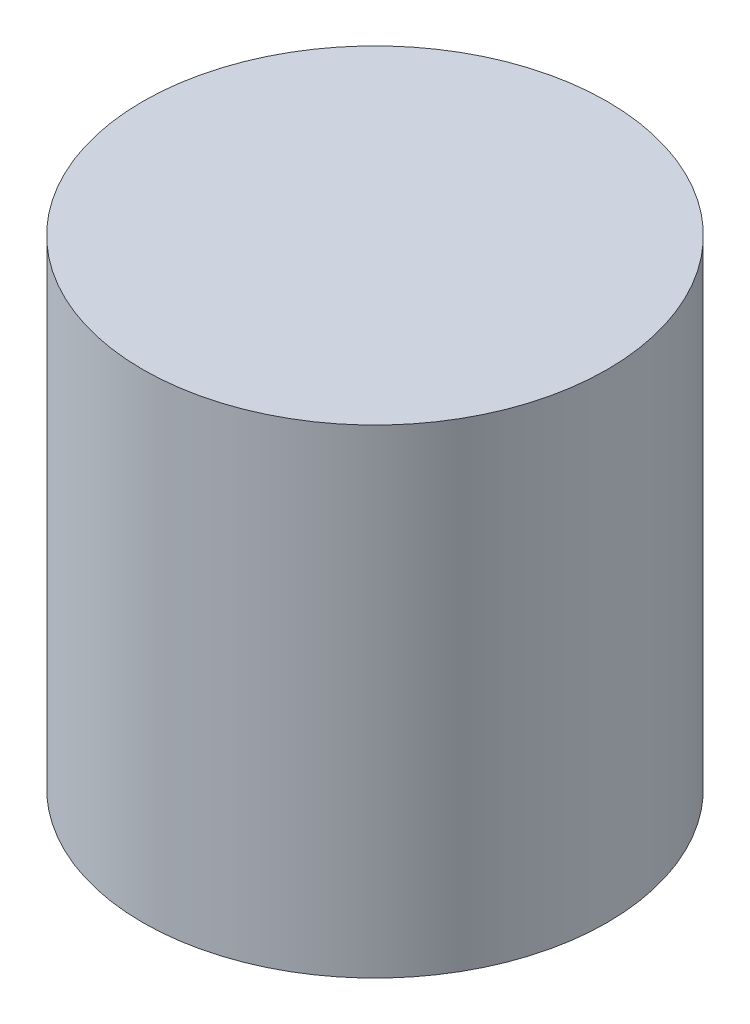
SolidWorks part; units mm, degrees
material "AISI 1035 Steel (SS)"
ref_plane "Front Plane" through (0, 0, 0) normal (0, 0, 1) x (1, 0, 0)
ref_plane "Top Plane" through (0, 0, 0) normal (0, 1, 0) x (1, 0, 0)
ref_plane "Right Plane" through (0, 0, 0) normal (1, 0, 0) x (0, 0, -1)
sketch "Sketch2" plane through (0, 0, 0) normal (0, 1, 0) x (1, 0, 0)
  circle A0 centre (0, 0) radius 32
extrude "Boss-Extrude1" add sketch "Sketch2" along normal blind 66
